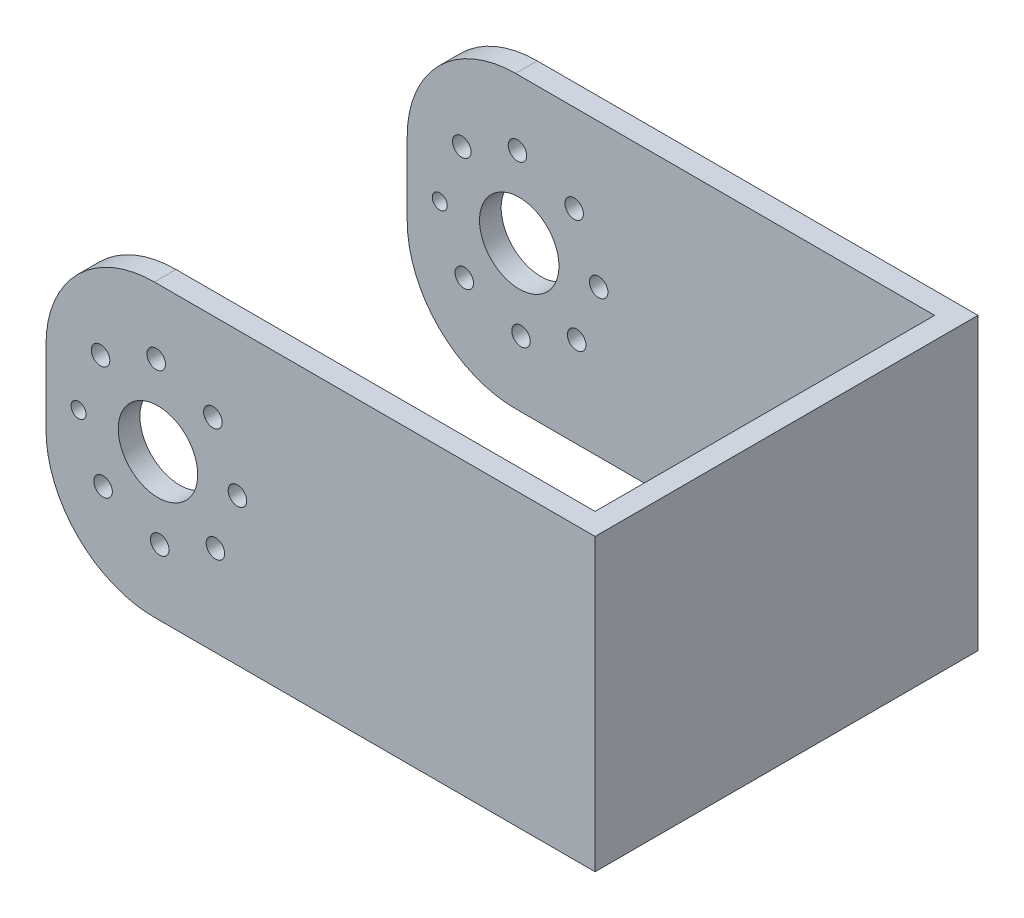
SolidWorks part; units mm, degrees
material "Aluminium 1050"
ref_plane "Front Plane" through (0, 0, 0) normal (0, 0, 1) x (1, 0, 0)
ref_plane "Top Plane" through (0, 0, 0) normal (0, 1, 0) x (1, 0, 0)
ref_plane "Right Plane" through (0, 0, 0) normal (1, 0, 0) x (0, 0, -1)
sketch "Sketch1" plane through (0, 0, 0) normal (0, 1, 0) x (1, 0, 0)
  line L0 (0, 0) -> (76, 0)
  line L1 (76, 0) -> (76, 53)
  line L2 (76, 53) -> (0, 53)
  line L3 (0, 53) -> (0, 0)
  line L4 (0, 3) -> (73, 3)
  line L5 (73, 3) -> (73, 50)
  line L6 (73, 50) -> (0, 50)
  dimension "D1" = 76
  dimension "D2" = 47
  dimension "D3" = 3
extrude "Boss-Extrude1" add sketch "Sketch1" along normal blind 40.2 contours L6 L5 L4 L3 L0 L1 L2
sketch "Sketch2" plane through (0, 0, 0) normal (0, 0, 1) x (1, 0, 0)
  line L0 (0, 40.2) -> (0, 0) construction
  line L1 (15.5, 40.2) -> (15.5, 0) construction
  circle A0 centre (15.5, 20.1) radius 5.5
  dimension "D2" = 11
  dimension "D1" = 15.5
extrude "Cut-Extrude1" cut sketch "Sketch2" against normal through all both and the other way through all
fillet "Fillet1" radius 15 4 edges at (0, 0, -1.5) (0, 40.2, -1.5) (0, 0, -51.5) (0, 40.2, -51.5)
sketch "Sketch3" plane through (0, 40.2, 0) normal (0, 1, 0) x (1, 0, 0)
  line L0 (87.5812, 25.2) -> (-15.8677, 25.2)
sketch "Sketch4" plane through (0, 0, -50) normal (0, 0, 1) x (1, 0, 0)
  circle A0 centre (15.7464, 9.1028) radius 1.2812
  circle A1 centre (7.898, 12.1496) radius 1.2812
  circle A2 centre (4.5028, 19.6078) radius 1.0354
  circle A3 centre (7.5496, 27.702) radius 1.2812
  circle A4 centre (23.4504, 12.498) radius 1.2812
  circle A5 centre (15.2536, 31.0972) radius 1.2812
  circle A6 centre (23.102, 28.0504) radius 1.2812
  circle A7 centre (26.4972, 20.3464) radius 1.2812
extrude "Cut-Extrude2" cut sketch "Sketch4" against normal through all both and the other way through all
